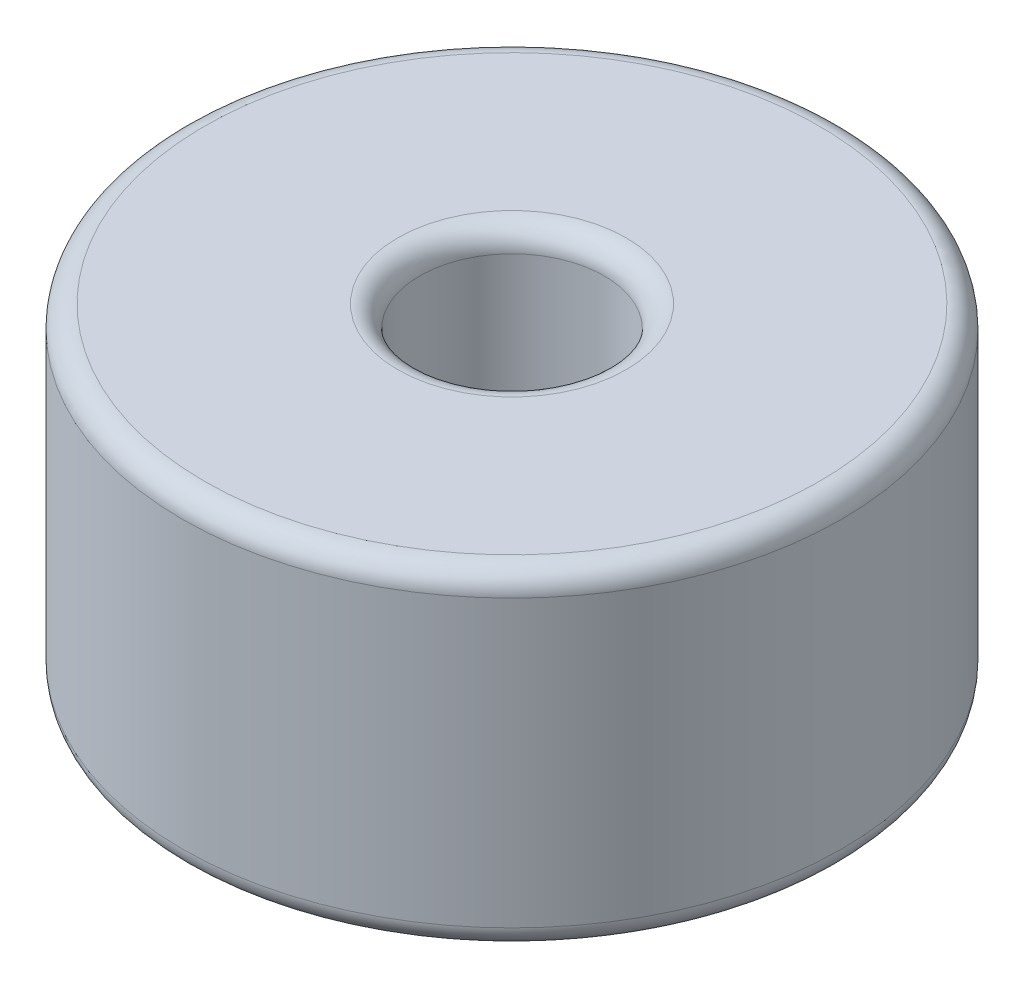
SolidWorks part; units mm, degrees
ref_plane "Front Plane" through (0, 0, 0) normal (0, 0, 1) x (1, 0, 0)
ref_plane "Top Plane" through (0, 0, 0) normal (0, 1, 0) x (1, 0, 0)
ref_plane "Right Plane" through (0, 0, 0) normal (1, 0, 0) x (0, 0, -1)
sketch "Sketch1" plane through (0, 0, 0) normal (0, 1, 0) x (1, 0, 0)
  circle A0 centre (0, 0) radius 2.1
  circle A1 centre (0, 0) radius 7.5
  dimension "D1" = 4.2
  dimension "D2" = 15
extrude "Boss-Extrude1" add sketch "Sketch1" along normal blind 7.5
fillet "Fillet1" radius 0.5 4 edges at (0, 0, 2.1) (0, 7.5, 2.1) (0, 0, 7.5) (0, 7.5, 7.5)
